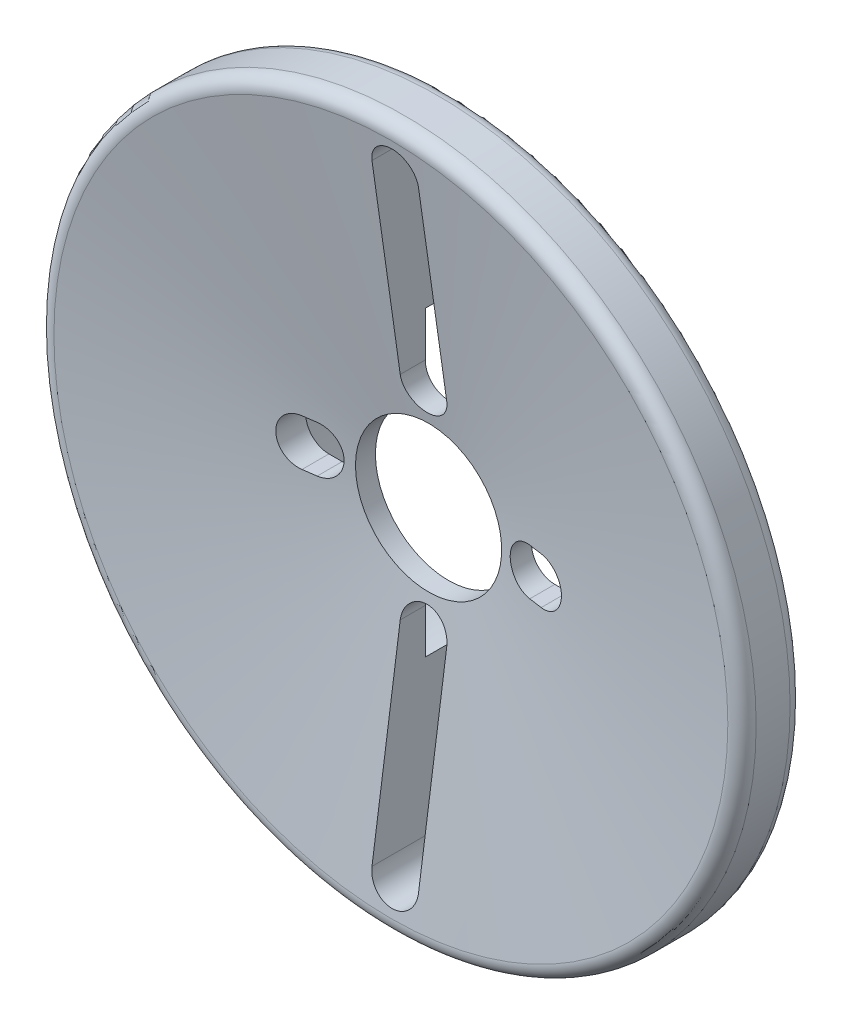
SolidWorks part; units mm, degrees
material "ABS"
ref_plane "Front Plane" through (0, 0, 0) normal (0, 0, 1) x (1, 0, 0)
ref_plane "Top Plane" through (0, 0, 0) normal (0, 1, 0) x (1, 0, 0)
ref_plane "Right Plane" through (0, 0, 0) normal (1, 0, 0) x (0, 0, -1)
sketch "Sketch1" plane through (0, 0, 0) normal (0, 0, 1) x (1, 0, 0)
  circle A0 centre (0, 0) radius 5.5
  circle A2 centre (0, 0) radius 26.5
  dimension "D1" = 11
  dimension "D2" = 21
extrude "Boss-Extrude1" add sketch "Sketch1" along normal blind 1.5
sketch "Sketch8" plane through (0, 0, 0) normal (0, 1, 0) x (1, 0, 0)
  line L0 (26.5, 0) -> (-26.5, 0) construction
  line L1 (26.5, 0) -> (-11.5, 0) construction
  line L2 (0, 0) -> (0, -17.1822) construction
  line L3 (-11.5, 0) -> (-11.5, 3.5)
  line L4 (-11.5, 3.5) -> (26.5, 0) construction
  line L5 (11.5, 3.5) -> (-26.5, 0) construction
  line L6 (11.5, 0) -> (11.5, 3.5) construction
  line L7 (11.5, 0) -> (-26.5, 0) construction
  line L8 (-11.5, 3.5) -> (-26.5, 0)
  line L9 (-26.5, 0) -> (-11.5, 0)
  line L10 (-26.5, -1.5) -> (26.5, -1.5) construction
  line L11 (5.5, -1.5) -> (26.5, -1.5)
  line L13 (26.5, -1.5) -> (26.5, -4.5)
  line L14 (26.5, -4.5) -> (5.5, -1.5)
  point P10 (11.5, 1.75)
  point P16 (5.5, -3.5)
  dimension "D1" = 23
  dimension "D2" = 3.5
  dimension "D3" = 3
revolve "Revolve2" add sketch "Sketch8" angle 360 about L2
sketch "Sketch7" plane through (0, 0, 0) normal (0, 0, 1) x (1, 0, 0)
  line L0 (1.75, -8) -> (1.75, -23)
  line L1 (-1.75, -8) -> (-1.75, -23)
  line L6 (8, 1.75) -> (9, 1.75)
  line L7 (8, -1.75) -> (9, -1.75)
  circle A0 centre (0, 0) radius 8 construction
  arc A1 (1.75, -8) -> (-1.75, -8) centre (0, -8) ccw
  arc A7 (8, 1.75) -> (8, -1.75) centre (8, 0) ccw
  arc A8 (-1.75, -23) -> (1.75, -23) centre (0, -23) ccw
  arc A11 (9, -1.75) -> (9, 1.75) centre (9, 0) ccw
  arc A12 (-8, -1.75) -> (-8, 1.75) centre (-8, 0) ccw [skipped]
  arc A13 (-1.75, 8) -> (1.75, 8) centre (0, 8) ccw [skipped]
  point P4 (11.207, 0)
  point P7 (0, 0)
  point P8 (0, 0)
  point P9 (0, 0)
  point P10 (8, 0)
  point P11 (0, 0)
  point P13 (8, 0)
  point P14 (0, 0)
  point P15 (0, 0)
  point P35 (0, 0)
  dimension "D1" = 16
  dimension "D2" = 3.5
  dimension "D4" = 15
  dimension "D5" = 1
  dimension "D6" = 90
  dimension "D3" = 4
extrude "holes" cut sketch "Sketch7" along normal through all both and the other way through all contours A7
fillet "Fillet2" radius 1 2 edges at (-26.5, 0, 0) (-26.5, 0, 4.5)
pattern_circular "holes-ptr" count 2 over 360 about axis through (0, 0, 0) along (0, 0, 1) of "holes"
